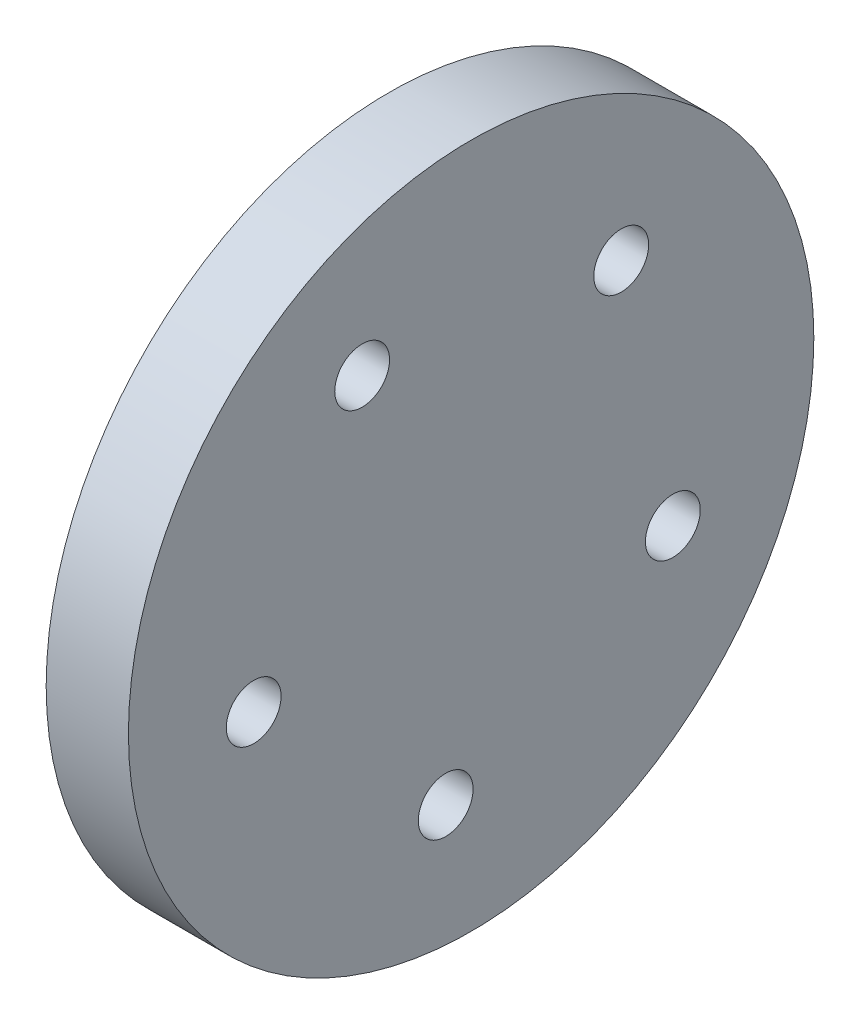
SolidWorks part; units mm, degrees
ref_plane "Front Plane" through (0, 0, 0) normal (0, 0, 1) x (1, 0, 0)
ref_plane "Top Plane" through (0, 0, 0) normal (0, 1, 0) x (1, 0, 0)
ref_plane "Right Plane" through (0, 0, 0) normal (1, 0, 0) x (0, 0, -1)
sketch "Sketch1" plane through (0, 0, 0) normal (1, 0, 0) x (0, 0, -1)
  circle A0 centre (0, 0) radius 23.8125
  dimension "D1" = 47.625
extrude "Wheel Body" add sketch "Sketch1" along normal blind 5.715
sketch "Sketch2" plane through (0, 0, 0) normal (1, 0, 0) x (0, 0, -1)
  circle A0 centre (0, 0) radius 2.8
  dimension "D1" = 5.6
extrude "C24T Spline" cut sketch "Sketch2" along normal blind 3.4544
sketch "Sketch3" plane through (0, 0, 0) normal (-1, 0, 0) x (0, 0, 1)
  circle A0 centre (-10.4294, 11.3497) radius 1.905
  circle A1 centre (7.5713, 13.4262) radius 1.905
  circle A2 centre (15.1087, -3.0518) radius 1.905
  circle A3 centre (1.7664, -15.3123) radius 1.905
  circle A4 centre (-14.0171, -6.4117) radius 1.905
  point P12 (0, 0)
  dimension "D1" = 3.81
  dimension "D2" = 5
extrude "Cut-Extrude2" cut sketch "Sketch3" against normal through all
